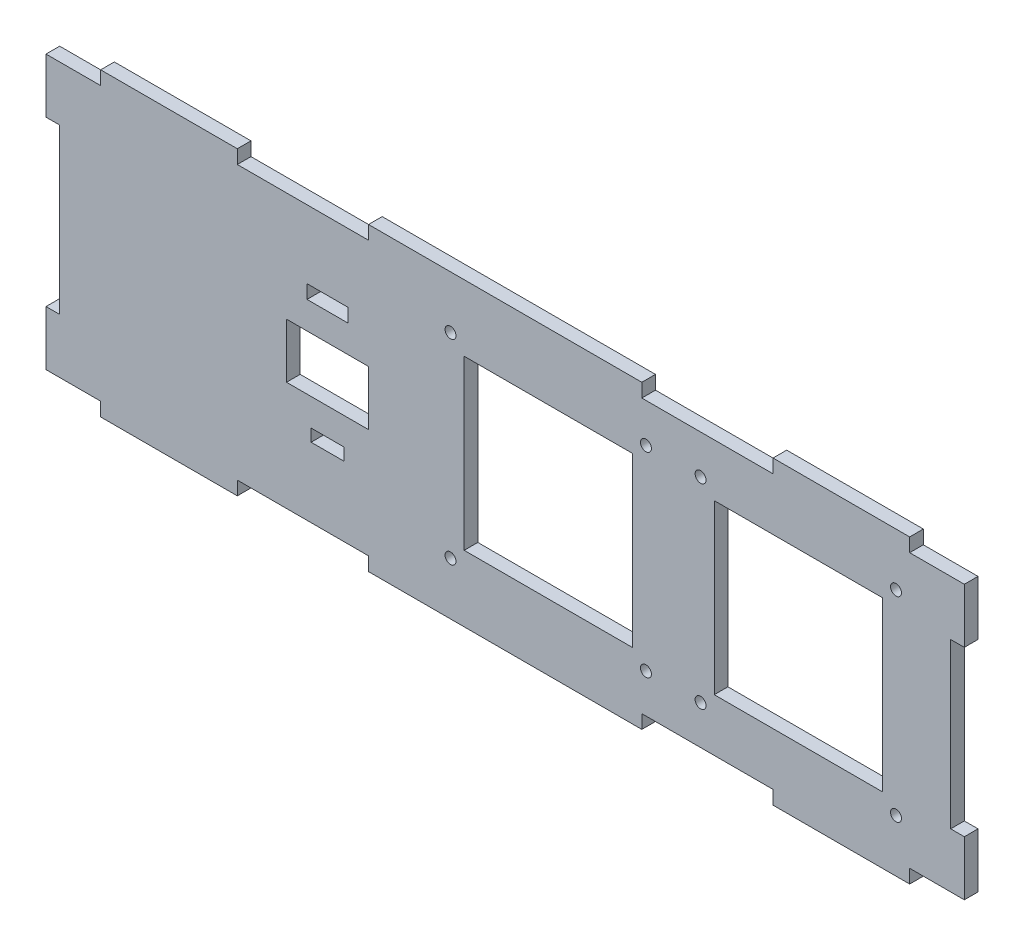
SolidWorks part; units mm, degrees
ref_plane "Front Plane" through (0, 0, 0) normal (0, 0, 1) x (1, 0, 0)
ref_plane "Top Plane" through (0, 0, 0) normal (0, 1, 0) x (1, 0, 0)
ref_plane "Right Plane" through (0, 0, 0) normal (1, 0, 0) x (0, 0, -1)
sketch "Sketch1" plane through (0, 0, 0) normal (0, 0, 1) x (1, 0, 0)
  line L0 (-168, 0) -> (168, 0) construction
  line L1 (168, -50) -> (-168, -50)
  line L2 (168, -50) -> (168, 50)
  line L3 (168, 50) -> (-168, 50)
  line L4 (-168, -50) -> (-168, 50)
  line L5 (168, -50) -> (-168, 50) construction
  line L6 (168, 50) -> (-168, -50) construction
  line L7 (0, 50) -> (0, -50) construction
  line L8 (-168, 30) -> (-163, 30)
  line L9 (-148, 50) -> (-98, 50)
  line L10 (-148, 50) -> (-148, 55)
  line L11 (-148, 55) -> (-98, 55)
  line L12 (-98, 50) -> (-98, 55)
  line L13 (0, 50) -> (-50, 50)
  line L15 (50, 55) -> (-50, 55)
  line L16 (-50, 50) -> (-50, 55)
  line L17 (-163, 30) -> (-163, -30)
  line L18 (-50, -50) -> (-50, -55)
  line L19 (50, -55) -> (-50, -55)
  line L20 (-168, -30) -> (-163, -30)
  line L21 (-148, -50) -> (-148, -55)
  line L22 (-98, -50) -> (-98, -55)
  line L23 (-148, -55) -> (-98, -55)
  line L24 (50, 50) -> (50, 55)
  line L25 (148, 50) -> (148, 55)
  line L26 (98, 50) -> (98, 55)
  line L27 (148, 55) -> (98, 55)
  line L28 (50, -50) -> (50, -55)
  line L29 (98, -50) -> (98, -55)
  line L30 (148, -50) -> (148, -55)
  line L31 (148, -55) -> (98, -55)
  line L32 (168, -30) -> (163, -30)
  line L33 (168, 30) -> (163, 30)
  line L34 (163, 30) -> (163, -30)
  line L35 (-50, 50) -> (50, 50)
  line L36 (-148, 50) -> (-98, 50)
  line L37 (98, 50) -> (148, 50)
  line L38 (168, 30) -> (168, -30)
  line L39 (148, -50) -> (98, -50)
  line L40 (50, -50) -> (-50, -50)
  line L41 (-98, -50) -> (-148, -50)
  line L42 (-168, 30) -> (-168, -30)
  line L54 (-20, 35.75) -> (51.5, -35.75) construction
  line L55 (-20, -35.75) -> (51.5, 35.75) construction
  line L56 (71.5, 35.75) -> (143, -35.75) construction
  line L57 (71.5, -35.75) -> (143, 35.75) construction
  line L58 (-65, 10) -> (-65, 35.75) construction
  line L59 (46.5, -30.75) -> (-15, -30.75)
  line L60 (46.5, -30.75) -> (46.5, 30.75)
  line L61 (46.5, 30.75) -> (-15, 30.75)
  line L62 (-15, -30.75) -> (-15, 30.75)
  line L63 (46.5, -30.75) -> (-15, 30.75) construction
  line L64 (46.5, 30.75) -> (-15, -30.75) construction
  line L65 (138, -30.75) -> (76.5, -30.75)
  line L66 (138, -30.75) -> (138, 30.75)
  line L67 (138, 30.75) -> (76.5, 30.75)
  line L68 (76.5, -30.75) -> (76.5, 30.75)
  line L69 (138, -30.75) -> (76.5, 30.75) construction
  line L70 (138, 30.75) -> (76.5, -30.75) construction
  line L71 (-80, -10) -> (-50, -10)
  line L72 (-80, -10) -> (-80, 10)
  line L73 (-80, 10) -> (-50, 10)
  line L74 (-50, -10) -> (-50, 10)
  line L75 (-80, -10) -> (-50, 10) construction
  line L76 (-80, 10) -> (-50, -10) construction
  line L77 (-72.5, 25) -> (-57.5, 25)
  line L81 (-72.5, 20) -> (-72.5, 25)
  line L82 (-72.5, 20) -> (-57.5, 20)
  line L83 (-65, 10) -> (-65, -50) construction
  line L84 (-65, 35.75) -> (-65, 50) construction
  line L85 (-59, -20) -> (-71, -20)
  line L86 (-71, -20) -> (-71, -24.5)
  line L87 (-71, -24.5) -> (-59, -24.5)
  line L88 (-59, -20) -> (-59, -24.5)
  line L89 (-57.5, 20) -> (-57.5, 25)
  circle A0 centre (-20, 35.75) radius 2
  circle A1 centre (51.5, 35.75) radius 2
  circle A2 centre (-20, -35.75) radius 2
  circle A3 centre (51.5, -35.75) radius 2
  circle A4 centre (71.5, 35.75) radius 2
  circle A5 centre (143, 35.75) radius 2
  circle A6 centre (71.5, -35.75) radius 2
  circle A7 centre (143, -35.75) radius 2
  point P0 (0, 0)
  point P24 (-163, 0)
  point P31 (0, 55)
  point P37 (0, -55)
  point P61 (15.75, 0)
  point P66 (107.25, 0)
  point P75 (-65, 0)
  point P86 (-65, 25)
  point P93 (-65, -24.5)
  point P94 (-65, -20)
  point P96 (-65, 20)
  dimension "D17" = 61.5
  dimension "D1" = 100
  dimension "D2" = 336
  dimension "D3" = 5
  dimension "D4" = 5
  dimension "D5" = 50
  dimension "D6" = 50
  dimension "D7" = 5
  dimension "D8" = 30
  dimension "D9" = 20
  dimension "D10" = 20
  dimension "D12" = 71.5
  dimension "D13" = 71.5
  dimension "D15" = 71.5
  dimension "D16" = 71.5
  dimension "D20" = 20
  dimension "D21" = 30
  dimension "D22" = 5
  dimension "D23" = 7.5
  dimension "D24" = 10
  dimension "D25" = 6
  dimension "D26" = 4.5
  dimension "D27" = 10
extrude "Boss-Extrude1" add sketch "Sketch1" along normal blind 5 contours L34 L33 L2 L3 L4 L8 L17 L20 L1 L32 | L28 L1 L18 L19 | L31 L30 L1 L29 | L25 L27 L26 L3 | L3 L12 L11 L10 | L23 L22 L41 L21 | L35 L24 L15 L16
